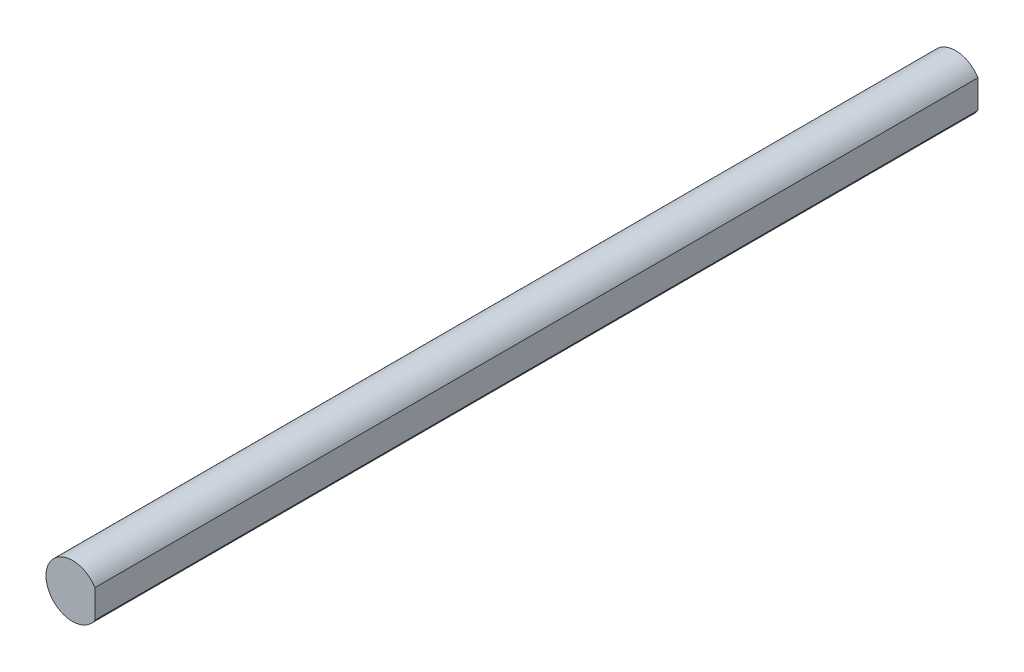
SolidWorks part; units mm, degrees
material "AISI 1045 Steel, cold drawn"
ref_plane "Frontal Plane" through (0, 0, 0) normal (0, 0, 1) x (1, 0, 0)
ref_plane "Horizontal Plane" through (0, 0, 0) normal (0, 1, 0) x (1, 0, 0)
ref_plane "Profile Plane" through (0, 0, 0) normal (1, 0, 0) x (0, 0, -1)
sketch "Sketch1" plane through (0, 0, 0) normal (0, 0, 1) x (1, 0, 0)
  circle A0 centre (0, 0) radius 3
  dimension "D1" = 6
extrude "Boss-Extrude1" add sketch "Sketch1" along normal blind 100
sketch "Sketch2" plane through (0, 0, 100) normal (0, 0, 1) x (1, 0, 0)
  line L0 (2.54, 1.5964) -> (2.54, -1.5964)
  arc A0 (2.54, 1.5964) -> (2.54, -1.5964) centre (0, 0) cw
  circle A1 centre (0, 0) radius 3 construction
  circle A2 centre (0, 0) radius 3 construction
  point P6 (3, 0)
  dimension "D1" = 2.54
extrude "Cut-Extrude1" cut sketch "Sketch2" against normal through all
sketch "Sketch4" [suppressed] plane through (0, 0, 100) normal (0, 0, 1) x (1, 0, 0)
  circle A0 centre (0, 0) radius 3 construction
  arc A1 (2.54, 1.5964) -> (2.54, -1.5964) centre (0, 0) ccw construction
equation "\"BaseL\"= 6ft"
equation "\"BaseW\"= 5.5in"
equation "\"BaseThickness\"= 1in"
equation "\"RailGap\"= 4cm"
equation "\"SlidePlateL\"= 8cm"
equation "\"SlidePlateW\"= 11cm"
equation "\"SlidePlateThickness\"= 5mm"
equation "\"SlidePlateClearance\"= 1cm"
equation "\"BoxThickness\"= .5cm"
equation "\"BoxX\"= \"RailGap\" + 30mm"
equation "\"BoxH\"= 2cm + \"SlidePlateClearance\" + \"SlidePlateThickness\" + 3cm"
equation "\"PulleyRadius\"= 15.1mm"
equation "\"PulleyH\"= 30mm + 21.4056mm - 2.5mm"
equation "\"PulleyShaftDiameter\"= .3125in"
equation "\"PulleyShaftL\"= 4in"
equation "\"PulleyShaft2L\"= 3in"
equation "\"MotorL\"= 4.43in"
equation "\"MotorRadius\"= 1.291in"
equation "\"MotorShaftRadius\"= .15625in"
equation "\"MotorShaftL\"= 1.75in"
equation "\"HeadstoneThickness\"= 7.5mm"
equation "\"BeltL\"= 1500mm + \"80\""
equation "\"BeltThickness\"= 2.5mm"
equation "\"BeltW\"= .375in"
equation "\"BeltLockH\"= \"PulleyH\" + 19.4056mm - (\"SlidePlateThickness\" + \"SlidePlateClearance\" + 15mm + 5mm)"
equation "\"EncoderL\"= 33mm"
equation "\"EncoderRadius\"= 19mm"
equation "\"EncoderShaftRadius\"= 3mm"
equation "\"EncoderShaftL\"= 15mm"
equation "\"PendulumShaftL\"= \"100mm\" "
equation "\"PendulumShaftRadius\"= 3mm"
equation "\"RodL\"= 39in"
equation "\"RodRadius\"= 3mm"
equation "\"D1@Sketch1\"=\"PendulumShaftRadius\"*2"
equation "\"D1@Boss-Extrude1\"=\"PendulumShaftL\""
